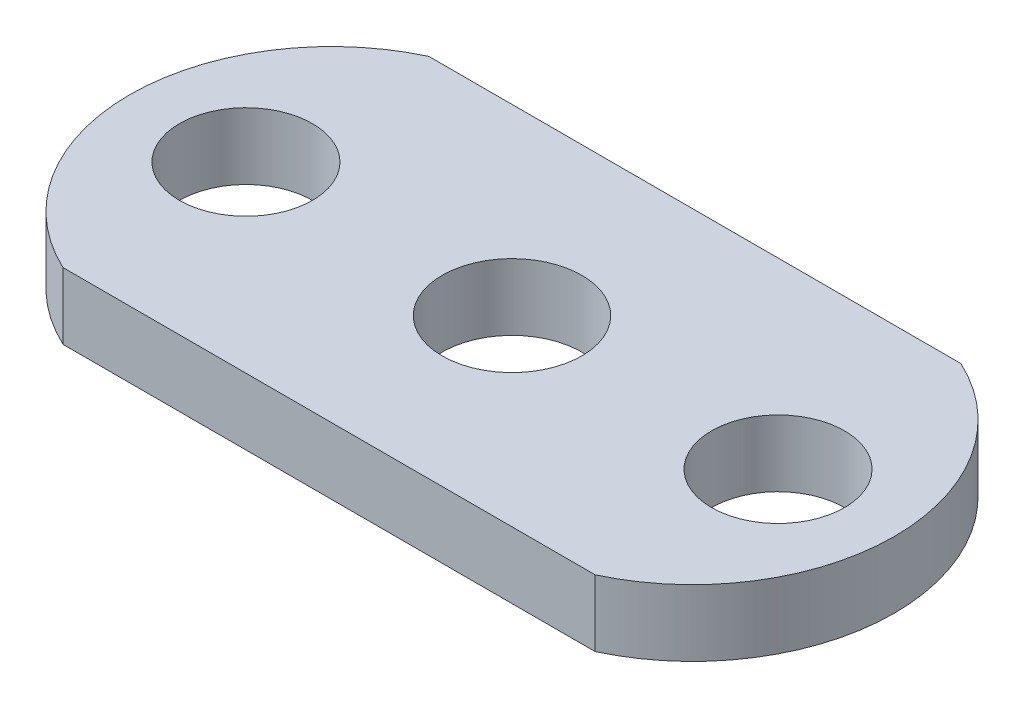
SolidWorks part; units mm, degrees
ref_plane "Alzado" through (0, 0, 0) normal (0, 0, 1) x (1, 0, 0)
ref_plane "Planta" through (0, 0, 0) normal (0, 1, 0) x (1, 0, 0)
ref_plane "Vista lateral" through (0, 0, 0) normal (1, 0, 0) x (0, 0, -1)
sketch "Croquis1" plane through (0, 0, 0) normal (0, 1, 0) x (1, 0, 0)
  line L0 (-11.5, 0) -> (11.5, 0) construction
  line L1 (8, -5.5) -> (8, 5.5) construction
  line L2 (-8, -5.5) -> (-8, 5.5) construction
  line L3 (-8, 5.5) -> (8, 5.5)
  line L4 (-8, -5.5) -> (8, -5.5)
  arc A0 (-8, -5.5) -> (-8, 5.5) centre (-5.4286, 0) cw
  arc A1 (8, 5.5) -> (8, -5.5) centre (5.4286, 0) cw
  circle A2 centre (8, 0) radius 2
  circle A3 centre (0, 0) radius 2.1
  circle A4 centre (-8, 0) radius 2
  point P4 (0, 0)
  point P7 (8, 0)
  point P10 (-8, 0)
  point P12 (11.5, 0)
  dimension "D6" = 4
  dimension "D7" = 4.2
  dimension "D8" = 4
  dimension "D1" = 23
  dimension "D2" = 3.5
  dimension "D3" = 11
  dimension "D4" = 11
  dimension "D5" = 3.5
extrude "Saliente-Extruir1" add sketch "Croquis1" along normal blind 2
